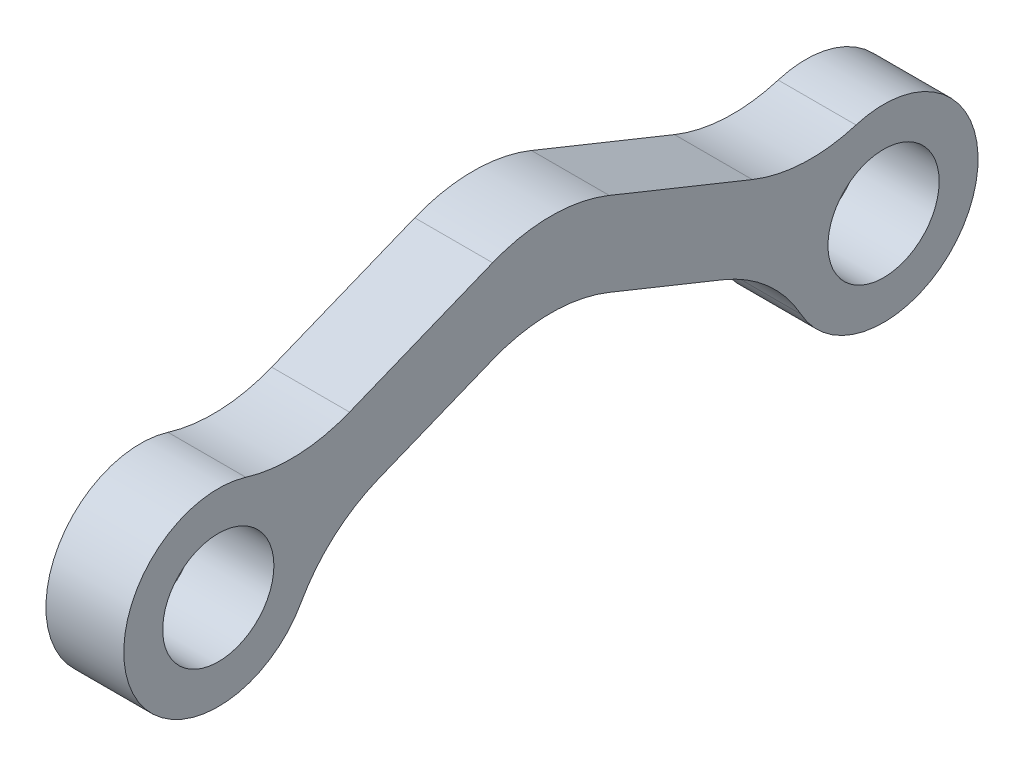
SolidWorks part; units mm, degrees
material "ABS"
ref_plane "Front Plane" through (0, 0, 0) normal (0, 0, 1) x (1, 0, 0)
ref_plane "Top Plane" through (0, 0, 0) normal (0, 1, 0) x (1, 0, 0)
ref_plane "Right Plane" through (0, 0, 0) normal (1, 0, 0) x (0, 0, -1)
sketch "Sketch1" plane through (0, 0, 0) normal (1, 0, 0) x (0, 0, -1)
  line L0 (0, 0) -> (-36.65, 0) construction
  line L1 (-34.2927, 6.1012) -> (-25.1061, 9.8128)
  line L2 (0, 0) -> (-21.36, 8.63) construction
  line L3 (-32.4196, 1.4653) -> (-25.1061, 4.4202)
  line L4 (-8.4273, 6.1012) -> (-17.6139, 9.8128)
  line L5 (-10.3004, 1.4653) -> (-17.6139, 4.4202)
  line L6 (-21.36, 11.3263) -> (-21.36, -8.5857) construction
  circle A0 centre (0, 0) radius 3.57
  arc A1 (-1.9739, -5.7401) -> (-1.9739, 5.7401) centre (0, 0) ccw construction
  arc A4 (-5.3057, -2.9487) -> (-1.7682, 5.8067) centre (0, 0) ccw
  arc A5 (-37.4143, -2.9487) -> (-40.9518, 5.8067) centre (-42.72, 0) cw
  arc A6 (-34.2927, 6.1012) -> (-40.9518, 5.8067) centre (-38.0387, 15.373) cw
  arc A7 (-32.4196, 1.4653) -> (-37.4143, -2.9487) centre (-28.6736, -7.8066) ccw
  arc A8 (-10.3004, 1.4653) -> (-5.3057, -2.9487) centre (-14.0464, -7.8066) cw
  arc A9 (-8.4273, 6.1012) -> (-1.7682, 5.8067) centre (-4.6813, 15.373) ccw
  arc A10 (-17.6139, 9.8128) -> (-25.1061, 9.8128) centre (-21.36, 0.541) ccw
  arc A11 (-17.6139, 4.4202) -> (-25.1061, 4.4202) centre (-21.36, -4.8517) ccw
  circle A12 centre (-42.72, 0) radius 3.57
  point P11 (-38.528, 4.39)
  point P20 (-36.655, -0.2459)
  point P23 (-6.065, -0.2459)
  point P26 (-4.192, 4.39)
  point P32 (-21.36, 5.9337)
  dimension "D1" = 7.14
  dimension "D2" = 6.07
  dimension "D4" = 7.14
  dimension "D5" = 2.5
  dimension "D7" = 22
  dimension "D3" = 10
  dimension "D6" = 21.36
  dimension "D8" = 22
  dimension "D9" = 21.36
  dimension "D10" = 42.72
extrude "Boss-Extrude1" add sketch "Sketch1" along normal blind 5
